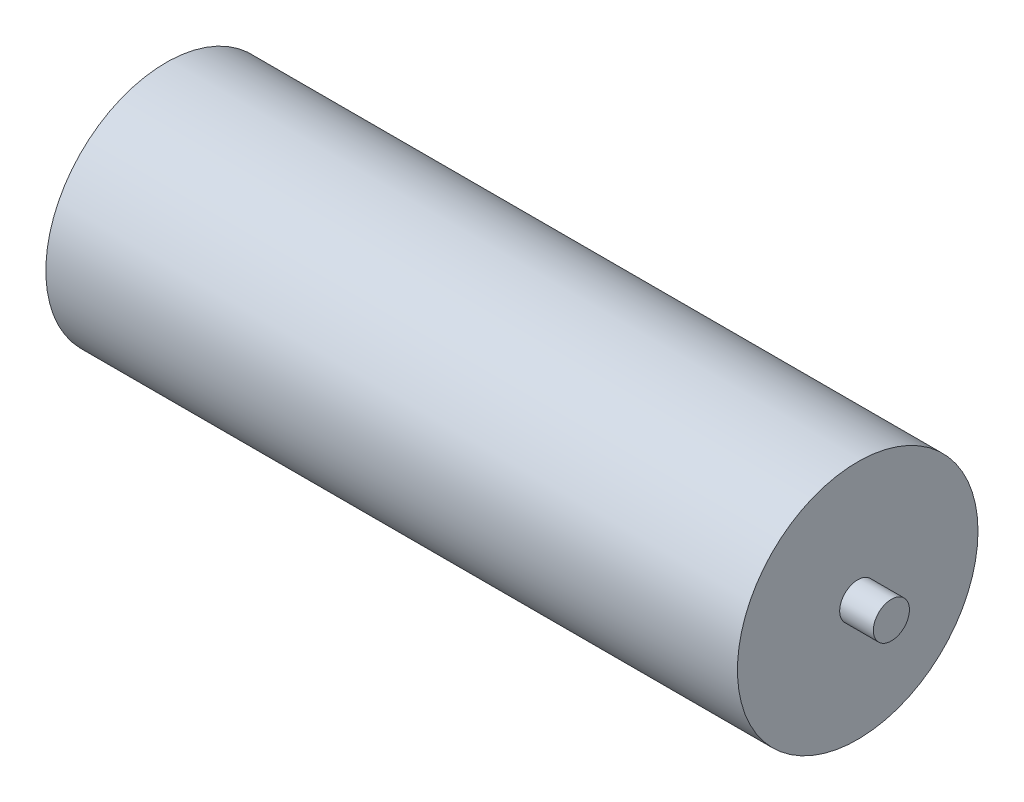
SolidWorks part; units mm, degrees
ref_plane "Front Plane" through (0, 0, 0) normal (0, 0, 1) x (1, 0, 0)
ref_plane "Top Plane" through (0, 0, 0) normal (0, 1, 0) x (1, 0, 0)
ref_plane "Right Plane" through (0, 0, 0) normal (1, 0, 0) x (0, 0, -1)
sketch "Sketch1" plane through (0, 0, 0) normal (1, 0, 0) x (0, 0, -1)
  circle A0 centre (0, 0) radius 25.4
  dimension "D1" = 50.8
extrude "Boss-Extrude1" add sketch "Sketch1" along normal blind 146.05
sketch "Sketch2" plane through (146.05, 0, 0) normal (1, 0, 0) x (0, 0, -1)
  circle A0 centre (0, 0) radius 3.81
  dimension "D1" = 7.62
extrude "Boss-Extrude2" add sketch "Sketch2" along normal blind 7.112
